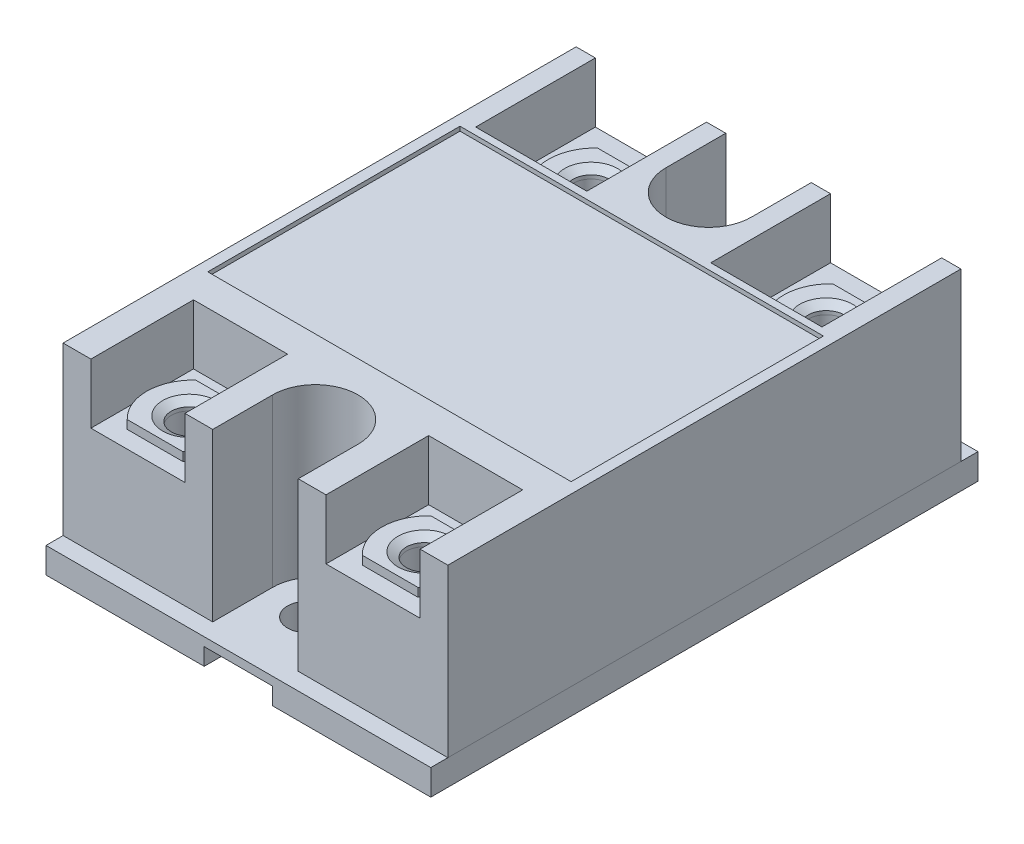
SolidWorks part; units mm, degrees
ref_plane "Front" through (0, 0, 0) normal (0, 0, 1) x (1, 0, 0)
ref_plane "Top" through (0, 0, 0) normal (0, 1, 0) x (1, 0, 0)
ref_plane "Right" through (0, 0, 0) normal (1, 0, 0) x (0, 0, -1)
sketch "Sketch1" plane through (0, 0, 0) normal (0, 1, 0) x (1, 0, 0)
  line L0 (0, 0) -> (0, 60)
  line L1 (0, 0) -> (17.5, 0)
  line L2 (17.5, 0) -> (17.5, 7)
  line L3 (27.5, 0) -> (27.5, 7)
  line L4 (27.5, 0) -> (45, 0)
  line L5 (45, 0) -> (45, 60)
  line L6 (0, 60) -> (17.5, 60)
  line L7 (17.5, 0) -> (27.5, 0) construction
  line L8 (17.5, 60) -> (17.5, 53)
  line L9 (45, 60) -> (27.5, 60)
  line L10 (27.5, 60) -> (27.5, 53)
  arc A0 (27.5, 7) -> (17.5, 7) centre (22.5, 7) ccw
  arc A1 (17.5, 53) -> (27.5, 53) centre (22.5, 53) ccw
  dimension "D1" = 60
  dimension "D2" = 17.5
  dimension "D3" = 7
  dimension "D4" = 10
extrude "Boss-Extrude1" add sketch "Sketch1" along normal blind 19.5
sketch "Sketch2" plane through (0, 19.5, 0) normal (0, 1, 0) x (1, 0, 0)
  line L0 (0, 0) -> (17.5, 0) construction
  line L1 (3.25, 0) -> (14.25, 0)
  line L2 (3.25, 0) -> (3.25, 12)
  line L3 (3.25, 12) -> (14.25, 12)
  line L4 (14.25, 0) -> (14.25, 12)
  line L5 (0, 60) -> (0, 0) construction
  line L7 (22.5, 48) -> (22.5, 12) construction
  line L8 (17.5, 60) -> (0, 60) construction
  line L10 (30.75, 0) -> (30.75, 12)
  line L11 (41.75, 12) -> (30.75, 12)
  line L12 (41.75, 0) -> (41.75, 12)
  line L13 (41.75, 0) -> (30.75, 0)
  line L14 (2.25, 60) -> (15.25, 60)
  line L15 (2.25, 60) -> (2.25, 46)
  line L16 (2.25, 46) -> (15.25, 46)
  line L17 (15.25, 60) -> (15.25, 46)
  line L19 (42.75, 46) -> (29.75, 46)
  line L20 (29.75, 60) -> (29.75, 46)
  line L21 (42.75, 60) -> (29.75, 60)
  line L23 (42.75, 60) -> (42.75, 46)
  arc A0 (17.5, 53) -> (27.5, 53) centre (22.5, 53) ccw construction
  arc A1 (27.5, 7) -> (17.5, 7) centre (22.5, 7) ccw construction
  dimension "D1" = 11
  dimension "D2" = 3.25
  dimension "D3" = 12
  dimension "D4" = 13
  dimension "D5" = 14
  dimension "D6" = 2.25
extrude "Cut-Extrude1" cut sketch "Sketch2" against normal blind 7
sketch "Sketch6" plane through (0, 0, 0) normal (0, 1, 0) x (1, 0, 0)
  line L1 (0, -2) -> (45, -2)
  line L2 (0, -2) -> (0, 62)
  line L3 (0, 62) -> (45, 62)
  line L4 (45, -2) -> (45, 62)
  line L6 (0, 0) -> (17.5, 0) construction
  line L7 (0, 60) -> (0, 0) construction
  line L8 (22.5, 55.5) -> (22.5, 54) construction
  line L9 (24.75, 55.5) -> (24.75, 54)
  line L10 (20.25, 55.5) -> (20.25, 54)
  circle A0 centre (22.5, 6) radius 2.25
  arc A1 (24.75, 55.5) -> (20.25, 55.5) centre (22.5, 55.5) ccw
  arc A2 (20.25, 54) -> (24.75, 54) centre (22.5, 54) ccw
  point P12 (22.5, 54.75)
  dimension "D5" = 4.5
  dimension "D8" = 8
  dimension "D1" = 45
  dimension "D2" = 64
  dimension "D3" = 2
  dimension "D4" = 0
  dimension "D6" = 22.5
  dimension "D7" = 8
  dimension "D9" = 22.5
  dimension "D10" = 4.5
extrude "Boss-Extrude2" add sketch "Sketch6" against normal blind 3 separate body
sketch "Sketch7" plane through (0, 19.5, 0) normal (0, 1, 0) x (1, 0, 0)
  line L0 (22.5, 62) -> (22.5, -11.7233) construction
  line L1 (1.25, 45.1676) -> (43.75, 45.1676)
  line L2 (1.25, 45.1676) -> (1.25, 15.6676)
  line L3 (1.25, 15.6676) -> (43.75, 15.6676)
  line L4 (43.75, 45.1676) -> (43.75, 15.6676)
  line L5 (45, 62) -> (0, 62) construction
  point P8 (22.5, 45.1676)
  dimension "D1" = 42.5
  dimension "D2" = 29.5
extrude "Cut-Extrude2" cut sketch "Sketch7" against normal blind 0.5
hole_wizard "M5x0.8 Tapped Hole1" positions "Sketch13" profile "Sketch12" tap size "M5x0.8" standard "ANSI Metric"
sketch "Sketch13" plane through (0, 12.5, 0) normal (0, 1, 0) x (1, 0, 0)
  line L0 (30.75, 0) -> (41.75, 0) construction
  line L2 (30.75, 12) -> (30.75, 0) construction
  point P0 (36.25, 6)
  dimension "D1" = 6
  dimension "D2" = 5.5
sketch "Sketch12" plane through (36.25, 12.5, -6) normal (1, 0, 0) x (0, 0, 1)
  line L0 (0, 0) -> (0, 15.2618)
  line L1 (0, 15.2618) -> (2.1, 14)
  line L2 (2.1, 14) -> (2.1, 0)
  line L5 (2.1, 0) -> (0, 0)
  line L10 (0, 15.2618) -> (-2.1, 14) construction
  line L11 (0, -6.35) -> (0, 107.95) construction
  dimension "Tap Drill Dia." = 4.2
  dimension "Tap Drill Depth" = 14
  dimension "Drill Angle" = 118
cosmetic thread "Hole Thread1" parameters "D1"=10, "D2"=5
pattern_linear "LPattern1" count 2 spacing 27.5 along (-1, 0, 0) count 2 spacing 47 along (0, 0, -1) of "M5x0.8 Tapped Hole1"
sketch "Sketch14" plane through (0, 12.5, 0) normal (0, 1, 0) x (1, 0, 0)
  line L0 (5.5, 10) -> (12, 10)
  line L1 (5.5, 2) -> (12, 2)
  arc A0 (12, 10) -> (12, 2) centre (8.2251, 6) cw
  arc A1 (5.5, 10) -> (5.5, 2) centre (9.2749, 6) ccw
  circle A2 centre (8.75, 6) radius 2.1
  point P6 (8.75, 10)
  dimension "D4" = 4
  dimension "D5" = 5.5
  dimension "D1" = 6.5
  dimension "D2" = 8
  dimension "D3" = 0
extrude "Boss-Extrude3" add sketch "Sketch14" along normal blind 1 separate body
chamfer "Chamfer1" distance 1 angle 30 1 edges at (8.75, 13.5, -3.9)
pattern_linear "LPattern2" count 2 spacing 27.5 along (1, 0, 0) count 2 spacing 47 along (0, 0, -1) of bodies 111
sketch "Sketch15" plane through (0, -3, 0) normal (0, -1, 0) x (1, 0, 0)
  line L0 (0, 2) -> (45, 2) construction
  line L1 (18.5, 2) -> (26.5, 2)
  line L2 (18.5, 2) -> (18.5, -1)
  line L3 (18.5, -1) -> (26.5, -1)
  line L4 (26.5, 2) -> (26.5, -1)
  line L6 (45, -62) -> (0, -62) construction
  line L7 (26.5, -59) -> (18.5, -59)
  line L8 (26.5, -59) -> (26.5, -62)
  line L9 (26.5, -62) -> (18.5, -62)
  line L10 (18.5, -59) -> (18.5, -62)
  point P6 (22.5, 2)
  point P15 (22.5, -59)
  dimension "D1" = 8
  dimension "D2" = 3
  dimension "D3" = 8
  dimension "D4" = 3
extrude "Cut-Extrude3" cut sketch "Sketch15" against normal blind 2
